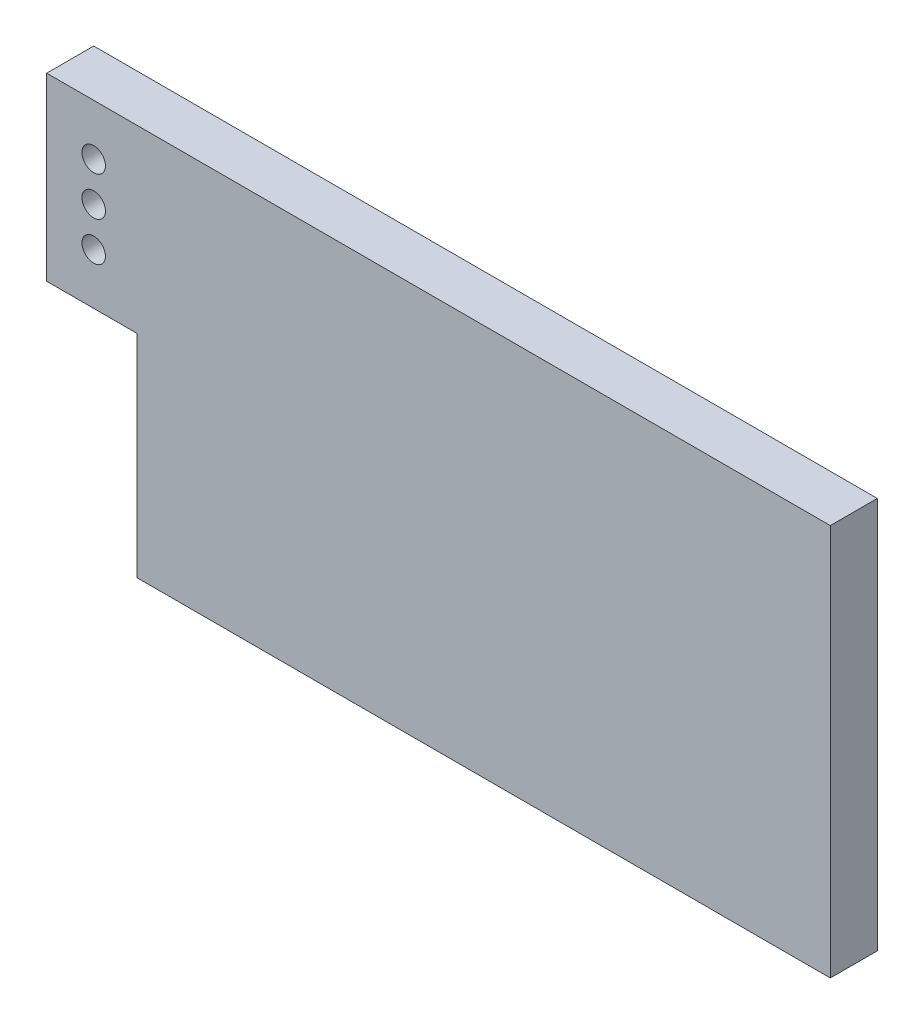
SolidWorks part; units mm, degrees
ref_plane "Front Plane" through (0, 0, 0) normal (0, 0, 1) x (1, 0, 0)
ref_plane "Top Plane" through (0, 0, 0) normal (0, 1, 0) x (1, 0, 0)
ref_plane "Right Plane" through (0, 0, 0) normal (1, 0, 0) x (0, 0, -1)
sketch "Sketch1" plane through (0, 0, 0) normal (0, 0, 1) x (1, 0, 0)
  line L1 (-5, -2.5) -> (5, -2.5)
  line L2 (-5, -2.5) -> (-5, 2.5)
  line L3 (-5, 2.5) -> (5, 2.5)
  line L4 (5, -2.5) -> (5, 2.5)
  line L5 (-5, -2.5) -> (5, 2.5) construction
  line L6 (-5, 2.5) -> (5, -2.5) construction
  point P0 (0, 0)
  dimension "D1" = 5
  dimension "D2" = 10
extrude "Boss-Extrude1" add sketch "Sketch1" along normal blind 0.6
sketch "Sketch2" plane through (0, 0, 0.6) normal (0, 0, 1) x (1, 0, 0)
  line L1 (-5, -2.5) -> (-3.85, -2.5)
  line L2 (-5, -2.5) -> (-5, 0.2)
  line L3 (-5, 0.2) -> (-3.85, 0.2)
  line L4 (-3.85, -2.5) -> (-3.85, 0.2)
  dimension "D1" = 2.7
  dimension "D2" = 1.15
extrude "Cut-Extrude1" cut sketch "Sketch2" against normal through all
sketch "Sketch3" plane through (0, 0, 0.6) normal (0, 0, 1) x (1, 0, 0)
  line L0 (-4.4, 2.5) -> (-4.4, 1.85) construction
  line L1 (5, 2.5) -> (-5, 2.5) construction
  line L2 (-4.4, 1.85) -> (-4.4, 1.35) construction
  line L3 (-4.4, 1.35) -> (-4.4, 0.85) construction
  line L4 (-4.4, 0.85) -> (-4.4, 0.2) construction
  line L5 (-3.85, 0.2) -> (-5, 0.2) construction
  line L6 (-4.4, 1.35) -> (-5, 1.35) construction
  line L7 (-5, 2.5) -> (-5, 0.2) construction
  circle A0 centre (-4.4, 1.85) radius 0.15
  circle A1 centre (-4.4, 1.35) radius 0.15
  circle A2 centre (-4.4, 0.85) radius 0.15
  dimension "D1" = 0.3
  dimension "D2" = 0.5
  dimension "D3" = 0.6
extrude "Cut-Extrude2" cut sketch "Sketch3" against normal through all
